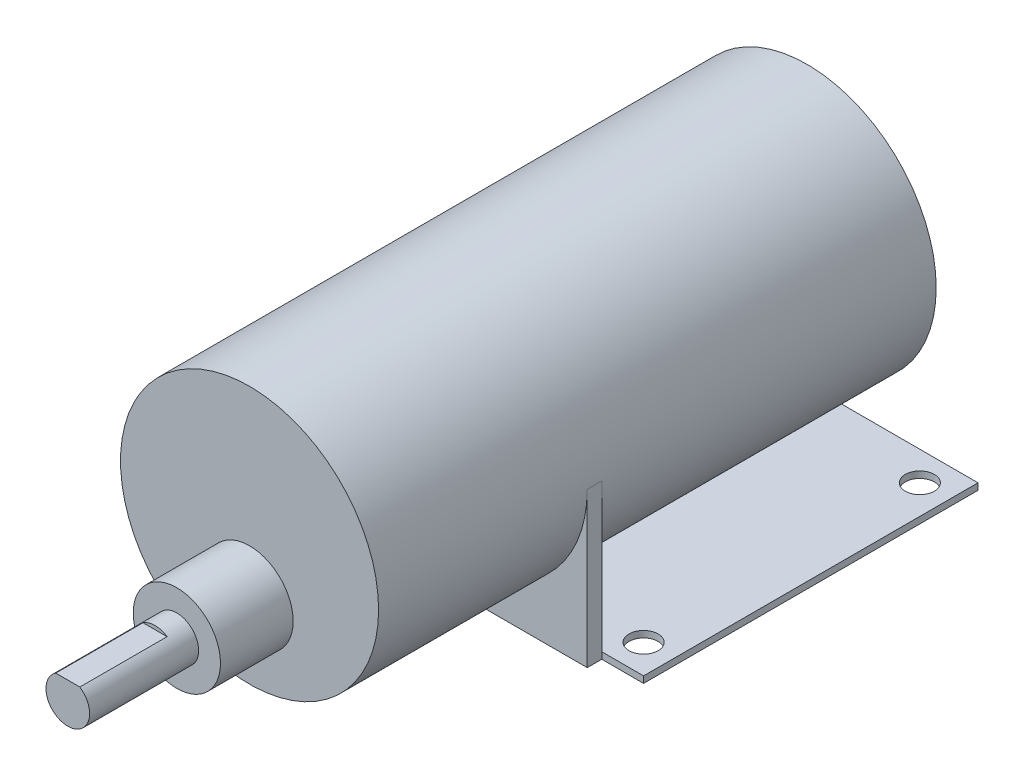
SolidWorks part; units mm, degrees
ref_plane "Front Plane" through (0, 0, 0) normal (0, 0, 1) x (1, 0, 0)
ref_plane "Top Plane" through (0, 0, 0) normal (0, 1, 0) x (1, 0, 0)
ref_plane "Right Plane" through (0, 0, 0) normal (1, 0, 0) x (0, 0, -1)
sketch "Sketch1" plane through (0, 0, 0) normal (0, 0, 1) x (1, 0, 0)
  circle A0 centre (0, 0) radius 17.75
  dimension "D1" = 35.5
extrude "Boss-Extrude1" add sketch "Sketch1" along normal blind 46
sketch "Sketch2" plane through (0, 0, 46) normal (0, 0, 1) x (1, 0, 0)
  line L4 (-17.75, -21.25) -> (17.75, -21.25)
  line L5 (-17.75, 0) -> (-17.75, -21.25)
  line L6 (17.75, 0) -> (17.75, -21.25)
  circle A0 centre (0, 0) radius 17.75 construction
  arc A2 (-17.75, 0) -> (17.75, 0) centre (0, 0) cw
  point P13 (0, -21.25)
extrude "Boss-Extrude2" add sketch "Sketch2" along normal blind 2
sketch "Sketch3" plane through (0, 0, 46) normal (0, 0, -1) x (-1, 0, 0)
  line L6 (0, 0) -> (0, -23.6229) construction
  line L8 (0, -21.25) -> (23.5, -21.25)
  line L9 (17.75, -21.25) -> (-17.75, -21.25) construction
  line L10 (0, -21.25) -> (-23.5, -21.25)
  line L11 (-23.5, -21.25) -> (-23.5, -20.35)
  line L12 (23.5, -21.25) -> (23.5, -20.35)
  line L13 (-23.5, -20.35) -> (23.5, -20.35)
  dimension "D1" = 0.9
  dimension "D2" = 0.9
extrude "Boss-Extrude3" add sketch "Sketch3" along normal blind 46
sketch "Sketch4" plane through (0, 0, 48) normal (0, 0, 1) x (1, 0, 0)
  circle A1 centre (0, 0) radius 17.75
extrude "Boss-Extrude4" add sketch "Sketch4" along normal blind 28.7
sketch "Sketch5" plane through (0, 0, 76.7) normal (0, 0, 1) x (1, 0, 0)
  line L0 (0, 0) -> (0, -23.1794) construction
  line L1 (-17.75, -21.25) -> (17.75, -21.25) construction
  circle A0 centre (0, -7.25) radius 6
  dimension "D1" = 14
extrude "Boss-Extrude5" add sketch "Sketch5" along normal blind 10
sketch "Sketch6" plane through (0, 0, 86.7) normal (0, 0, 1) x (1, 0, 0)
  circle A0 centre (0, -7.25) radius 3
extrude "Boss-Extrude6" add sketch "Sketch6" along normal blind 15
sketch "Sketch7" plane through (0, 0, 101.7) normal (0, 0, 1) x (1, 0, 0)
  line L0 (0, -4.25) -> (0, -4.75) construction
  line L1 (-1.6583, -4.75) -> (1.6583, -4.75)
  circle A0 centre (0, -7.25) radius 3 construction
  circle A1 centre (0, -7.25) radius 3 construction
  arc A2 (1.6583, -4.75) -> (-1.6583, -4.75) centre (0, -7.25) ccw
  point P11 (0, -4.75)
extrude "Cut-Extrude1" cut sketch "Sketch7" against normal blind 12
sketch "Sketch8" plane through (0, -21.25, 0) normal (0, -1, 0) x (-1, 0, 0)
  line L0 (17.75, -46) -> (23.5, -46) construction
  line L2 (-23.5, 0) -> (-23.5, -46) construction
  line L3 (-23.5, -46) -> (-17.75, -46) construction
  line L7 (-23.5, 0) -> (23.5, 0) construction
  line L8 (19.5, -4) -> (19.5, 0) construction
  line L12 (19.5, -4) -> (23.5, -4) construction
  line L13 (23.5, 0) -> (23.5, -46) construction
  line L14 (19.5, 0) -> (19.5, -4) construction
  circle A0 centre (19.5, -42) radius 2
  circle A1 centre (-19.5, -42) radius 2
  circle A2 centre (19.5, -4) radius 2
  circle A3 centre (-19.5, -4) radius 2
  dimension "D1" = 4
  dimension "D5" = 4
  dimension "D2" = 4
  dimension "D3" = 4
  dimension "D4" = 4
  dimension "D6" = 4
  dimension "D7" = 4
  dimension "D8" = 4
extrude "Cut-Extrude7" cut sketch "Sketch8" against normal blind 12
sketch "Sketch9" plane through (0, 0, 0) normal (1, 0, 0) x (0, 0, -1)
  line L0 (-101.7, -4.75) -> (-89.7, -4.75) construction
  line L1 (-89.7, -4.75) -> (-86.7, -4.75) construction
  line L2 (-86.7, -4.25) -> (-86.7, -10.25) construction
  line L3 (-86.7, -4.75) -> (-76.7, -4.75) construction
  line L4 (-76.7, 17.75) -> (-76.7, -17.75) construction
  line L5 (-76.7, -4.75) -> (0, -4.75) construction
  line L6 (0, -17.75) -> (0, 17.75) construction
  line L7 (-7.4505, 17.75) -> (-7.4505, -17.75) construction
  line L8 (0, 17.75) -> (-76.7, 17.75) construction
  line L9 (-46, -17.75) -> (0, -17.75) construction
  line L10 (0, -21.25) -> (-48, -21.25) construction
  line L11 (0, 17.75) -> (-101.7, 17.75) construction
  line L12 (-80.5546, -1.25) -> (-80.5546, -13.25) construction
  line L13 (-76.7, -1.25) -> (-86.7, -1.25) construction
  line L14 (-86.7, -13.25) -> (-76.7, -13.25) construction
  dimension "D1" = 12
  dimension "D2" = 3
  dimension "D3" = 10
  dimension "D4" = 76.7
